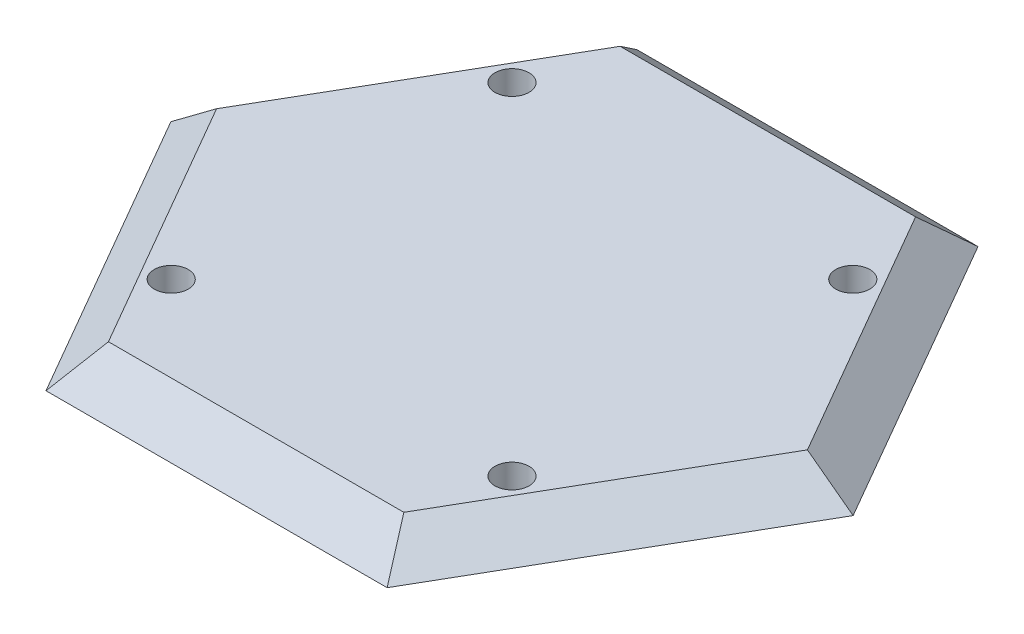
SolidWorks part; units mm, degrees
material "Beech"
ref_plane "Front Plane" through (0, 0, 0) normal (0, 0, 1) x (1, 0, 0)
ref_plane "Top Plane" through (0, 0, 0) normal (0, 1, 0) x (1, 0, 0)
ref_plane "Right Plane" through (0, 0, 0) normal (1, 0, 0) x (0, 0, -1)
sketch "Sketch1" plane through (0, 0, 0) normal (0, 1, 0) x (1, 0, 0)
  line L1 (50.0516, 0) -> (25.0258, 43.3459)
  line L2 (25.0258, 43.3459) -> (-25.0258, 43.3459)
  line L3 (-25.0258, 43.3459) -> (-50.0516, 0)
  line L4 (-50.0516, 0) -> (-25.0258, -43.3459)
  line L5 (-25.0258, -43.3459) -> (25.0258, -43.3459)
  line L6 (25.0258, -43.3459) -> (50.0516, 0)
  circle A0 centre (0, 0) radius 43.3459 construction
ref_plane "Plane6" through (0, 5, 0) normal (0, 1, 0) x (1, 0, 0)
sketch "Sketch2" plane through (0, 5, 0) normal (0, 1, 0) x (1, 0, 0)
  line L1 (43.3459, 0) -> (21.673, 37.5387)
  line L2 (21.673, 37.5387) -> (-21.673, 37.5387)
  line L3 (-21.673, 37.5387) -> (-43.3459, 0)
  line L4 (-43.3459, 0) -> (-21.673, -37.5387)
  line L5 (-21.673, -37.5387) -> (21.673, -37.5387)
  line L6 (21.673, -37.5387) -> (43.3459, 0)
  circle A0 centre (0, 0) radius 37.5387 construction
loft "Loft3" add profiles "Sketch1", "Sketch2"
sketch "Sketch4" plane through (0, 5, 0) normal (0, 1, 0) x (1, 0, 0)
  circle A0 centre (-25, 25) radius 2.5
extrude "Cut-Extrude1" cut sketch "Sketch4" against normal blind 5
sketch "Sketch5" plane through (0, 5, 0) normal (0, 1, 0) x (1, 0, 0)
  circle A0 centre (25, 25) radius 2.5
extrude "Cut-Extrude2" cut sketch "Sketch5" against normal blind 5
sketch "Sketch6" plane through (0, 5, 0) normal (0, 1, 0) x (1, 0, 0)
  circle A0 centre (-25, -25) radius 2.5
extrude "Cut-Extrude3" cut sketch "Sketch6" against normal blind 5
sketch "Sketch7" plane through (0, 5, 0) normal (0, 1, 0) x (1, 0, 0)
  circle A0 centre (25, -25) radius 2.5
extrude "Cut-Extrude4" cut sketch "Sketch7" against normal blind 5
